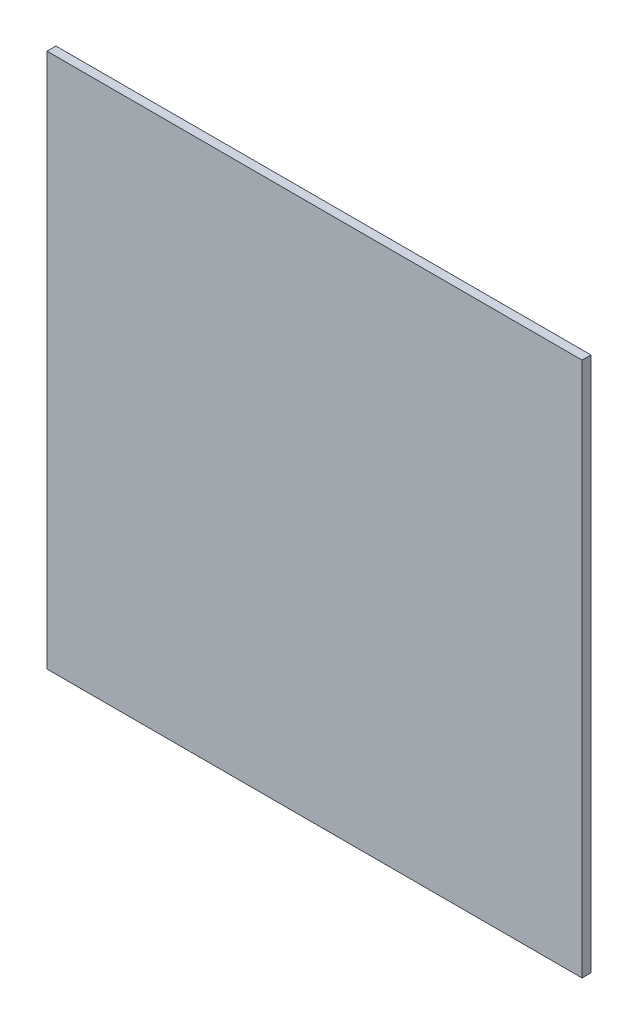
SolidWorks part; units mm, degrees
ref_plane "Plan de face" through (0, 0, 0) normal (0, 0, 1) x (1, 0, 0)
ref_plane "Plan de dessus" through (0, 0, 0) normal (0, 1, 0) x (1, 0, 0)
ref_plane "Plan de droite" through (0, 0, 0) normal (1, 0, 0) x (0, 0, -1)
sketch "Esquisse1" plane through (0, 0, 0) normal (0, 0, 1) x (1, 0, 0)
  line L1 (-150, 150) -> (150, 150)
  line L2 (-150, 150) -> (-150, -150)
  line L3 (-150, -150) -> (150, -150)
  line L4 (150, 150) -> (150, -150)
  line L5 (-150, 150) -> (150, -150) construction
  line L6 (-150, -150) -> (150, 150) construction
  point P0 (0, 0)
  dimension "D1" = 300
  dimension "D2" = 300
extrude "Boss.-Extru.1" add sketch "Esquisse1" along normal blind 5
